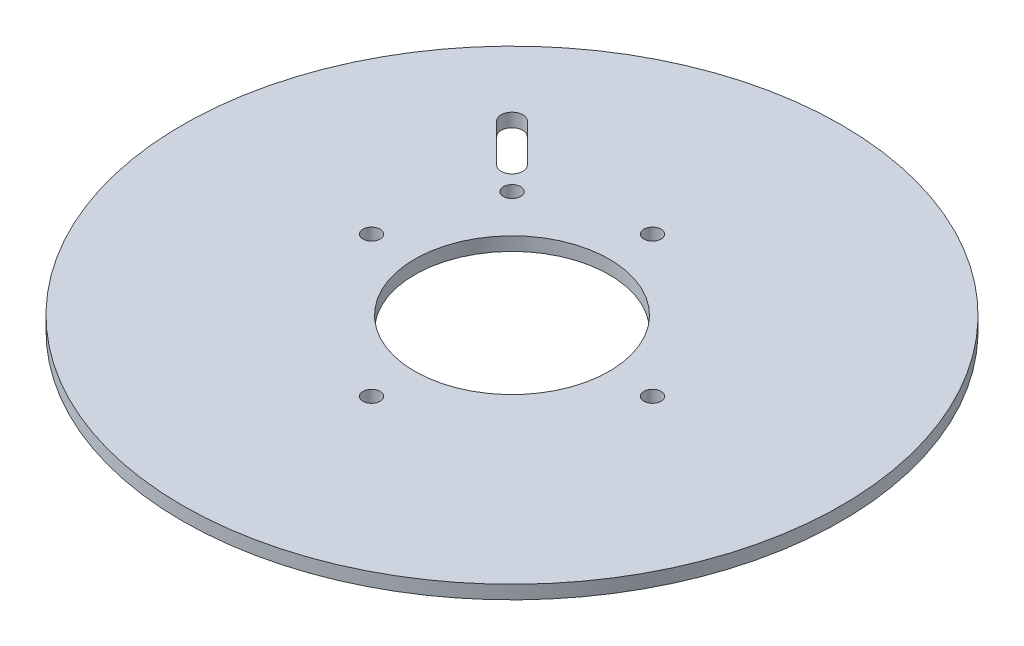
SolidWorks part; units mm, degrees
ref_plane "Front" through (0, 0, 0) normal (0, 0, 1) x (1, 0, 0)
ref_plane "Top" through (0, 0, 0) normal (0, 1, 0) x (1, 0, 0)
ref_plane "Right" through (0, 0, 0) normal (1, 0, 0) x (0, 0, -1)
sketch "Sketch1" plane through (0, 0, 0) normal (0, 1, 0) x (1, 0, 0)
  circle A0 centre (0, 0) radius 77.46
  dimension "D1" = 154.92
extrude "Boss-Extrude1" add sketch "Sketch1" along normal blind 3.175
sketch "Sketch2" plane through (0, 3.175, 0) normal (0, 1, 0) x (1, 0, 0)
  circle A0 centre (0, 0) radius 22.86
  dimension "D1" = 45.72
extrude "Cut-Extrude1" [suppressed] cut sketch "Sketch2" against normal through all
hole_wizard "M3 Clearance Hole1" [suppressed] positions "Sketch4" profile "Sketch3" hole size "M3" standard "ANSI Metric"
sketch "Sketch4" plane through (0, 3.175, 0) normal (0, 1, 0) x (1, 0, 0)
  circle A0 centre (0, 0) radius 27 construction
  point P0 (-27, 0)
  point P2 (0, 27)
  point P4 (27, 0)
  point P6 (0, -27)
  dimension "D1" = 54
sketch "Sketch3" plane through (-27, 3.175, 0) normal (1, 0, 0) x (0, 0, 1)
  line L0 (0, 0) -> (0, 3.175)
  line L1 (0, 3.175) -> (1.7, 3.175)
  line L2 (1.7, 3.175) -> (1.7, 0)
  line L5 (1.7, 0) -> (0, 0)
  line L11 (0, -6.35) -> (0, 107.95) construction
  dimension "Thru Hole Dia." = 3.4
  dimension "Thru Hole Depth" = 3.175
sketch "Sketch5" plane through (0, 0, 0) normal (0, -1, 0) x (-1, 0, 0)
  line L0 (0, 0) -> (116.3694, 0) construction
  line L1 (76.4147, 28.5) -> (66.4147, 28.5)
  line L2 (76.4147, 28.5) -> (76.4147, 31.5)
  line L3 (76.4147, 31.5) -> (66.4147, 31.5)
  line L4 (66.4147, 28.5) -> (66.4147, 31.5)
  line L5 (76.4147, 28.5) -> (66.4147, 31.5) construction
  line L6 (76.4147, 31.5) -> (66.4147, 28.5) construction
  line L7 (76.4147, -28.5) -> (76.4147, -31.5)
  line L8 (76.4147, -28.5) -> (66.4147, -28.5)
  line L9 (66.4147, -28.5) -> (66.4147, -31.5)
  line L10 (76.4147, -31.5) -> (66.4147, -31.5)
  circle A0 centre (0, 0) radius 77.46 construction
  point P0 (71.4147, 30)
  dimension "D1" = 3
  dimension "D2" = 10
  dimension "D3" = 30
extrude "Cut-Extrude2" [suppressed] cut sketch "Sketch5" against normal through all
hole_wizard "M3 Clearance Slot1" [suppressed] positions "Sketch7" profile "Sketch8" size "M3" standard "ANSI Metric"
sketch "Sketch7" plane through (0, 0, 0) normal (0, -1, 0) x (-1, 0, 0)
  line L0 (0, 0) -> (71.3755, 0) construction
  line L1 (55, -30) -> (25, -30) construction
  point P0 (40, -30)
  dimension "D1" = 40
  dimension "D2" = 30
  dimension "D3" = 30
sketch "Sketch8" plane through (-40, 0, 30) normal (1, 0, 0) x (0, 0, -1)
  line L0 (0, 0) -> (0, 26.4215)
  line L1 (0, 26.4215) -> (1.7, 25.4)
  line L2 (1.7, 25.4) -> (1.7, 0)
  line L5 (1.7, 0) -> (0, 0)
  line L10 (0, 26.4215) -> (-1.7, 25.4) construction
  line L11 (0, -6.35) -> (0, 107.95) construction
  dimension "Hole Dia." = 3.4
  dimension "Hole Depth" = 25.4
  dimension "Drill Angle" = 118
hole_wizard "M3 Clearance Hole2" [suppressed] positions "Sketch11" profile "Sketch12" hole size "M3" standard "ANSI Metric"
sketch "Sketch11" [suppressed] plane through (0, 3.175, 0) normal (0, 1, 0) x (1, 0, 0)
  line L0 (-53.3, -28.3) -> (-53.3, 14.1687) construction
  point P0 (-53.3, 30)
  dimension "D1" = 30
sketch "Sketch12" plane through (-53.3, 3.175, -30) normal (1, 0, 0) x (0, 0, 1)
  line L0 (0, 0) -> (0, 3.175)
  line L1 (0, 3.175) -> (1.7, 3.175)
  line L2 (1.7, 3.175) -> (1.7, 0)
  line L5 (1.7, 0) -> (0, 0)
  line L11 (0, -6.35) -> (0, 107.95) construction
  dimension "Thru Hole Dia." = 3.4
  dimension "Thru Hole Depth" = 3.175
sketch "Sketch13" [suppressed] plane through (0, 3.175, 0) normal (0, 1, 0) x (1, 0, 0)
  line L0 (0, 0) -> (0, 33.02) construction
  circle A0 centre (0, 0) radius 33.02 construction
  circle A1 centre (0, 0) radius 22.86 construction
  circle A2 centre (0, 33.02) radius 2.0193
  circle A3 centre (33.02, 0) radius 2.0193
  circle A4 centre (0, -33.02) radius 2.0193
  circle A5 centre (-33.02, 0) radius 2.0193
  point P16 (0, 0)
  dimension "D1" = 10.16
  dimension "D2" = 4.0386
  dimension "D3" = 4
extrude "Cut-Extrude3" [suppressed] cut sketch "Sketch13" against normal up to next
extrude "Cut-Extrude9" [suppressed] cut sketch "Sketch19" against normal through all
sketch "Sketch19" plane through (-73.7688, 3.175, -121.0804) normal (0, 1, 0) x (1, 0, 0)
  circle A1 centre (48.605, -95.9166) radius 2.0193 construction
  circle A3 centre (73.7688, -121.0804) radius 22.86 construction
  circle A4 centre (73.7688, -121.0804) radius 35.587 construction
  arc A5 (40.7129, -134.2614) -> (42.8303, -138.6656) centre (73.7688, -121.0804) ccw construction
  arc A6 (33.7184, -137.0504) -> (36.2838, -142.3866) centre (73.7688, -121.0804) ccw
  arc A7 (47.7074, -131.4723) -> (49.3768, -134.9446) centre (73.7688, -121.0804) ccw
  arc A8 (47.7074, -131.4723) -> (33.7184, -137.0504) centre (40.7129, -134.2614) ccw
  arc A9 (36.2838, -142.3866) -> (49.3768, -134.9446) centre (42.8303, -138.6656) ccw
  point P9 (41.6959, -136.4999)
extrude "Cut-Extrude10" cut sketch "Sketch20" against normal through all
sketch "Sketch20" plane through (-73.7688, 3.175, -121.0804) normal (0, 1, 0) x (1, 0, 0)
  line L0 (73.7688, -121.0804) -> (73.7688, -88.0604) construction
  circle A1 centre (73.7688, -121.0804) radius 77.46 construction
  circle A2 centre (73.7688, -121.0804) radius 22.86
  circle A3 centre (73.7688, -88.0604) radius 2.0193
  circle A4 centre (106.7888, -121.0804) radius 2.0193
  circle A5 centre (73.7688, -154.1004) radius 2.0193
  circle A6 centre (40.7488, -121.0804) radius 2.0193
  point P4 (73.7688, -98.2204)
  point P16 (73.7688, -121.0804)
extrude "Cut-Extrude11" cut sketch "Sketch21" against normal blind 3.175
sketch "Sketch21" plane through (-73.7688, 3.175, -121.0804) normal (0, 1, 0) x (1, 0, 0)
  line L0 (43.2169, -90.5284) -> (34.2366, -81.5481) construction
  line L1 (41.4208, -92.3245) -> (32.4406, -83.3442)
  line L2 (45.0129, -88.7324) -> (36.0327, -79.7521)
  arc A1 (41.4208, -92.3245) -> (45.0129, -88.7324) centre (43.2169, -90.5284) ccw construction
  arc A2 (41.4208, -92.3245) -> (45.0129, -88.7324) centre (43.2169, -90.5284) ccw
  arc A3 (36.0327, -79.7521) -> (32.4406, -83.3442) centre (34.2366, -81.5481) ccw
  point P3 (38.7267, -86.0383)
extrude "Cut-Extrude12" cut sketch "Sketch22" against normal through all
sketch "Sketch22" plane through (-73.7688, 3.175, -121.0804) normal (0, 1, 0) x (1, 0, 0)
  line L0 (43.2169, -90.5284) -> (48.605, -95.9166) construction
  arc A1 (41.4208, -92.3245) -> (45.0129, -88.7324) centre (43.2169, -90.5284) ccw construction
  circle A2 centre (48.605, -95.9166) radius 2.0193
extrude "Cut-Extrude13" [suppressed] cut sketch "Sketch23" against normal through all
sketch "Sketch23" plane through (-73.7688, 3.175, -121.0804) normal (0, 1, 0) x (1, 0, 0)
  circle A2 centre (73.7688, -121.0804) radius 22.86 construction
  circle A3 centre (48.605, -95.9166) radius 2.0193 construction
  circle A4 centre (73.7688, -121.0804) radius 35.587 construction
  arc A5 (40.5263, -133.7834) -> (43.5223, -139.8309) centre (73.7688, -121.0804) ccw construction
  arc A6 (34.406, -136.1222) -> (37.9536, -143.283) centre (73.7688, -121.0804) ccw
  arc A7 (46.6466, -131.4446) -> (49.091, -136.3787) centre (73.7688, -121.0804) ccw
  arc A8 (46.6466, -131.4446) -> (34.406, -136.1222) centre (40.5263, -133.7834) ccw
  arc A9 (37.9536, -143.283) -> (49.091, -136.3787) centre (43.5223, -139.8309) ccw
  point P9 (41.8806, -136.8783)
